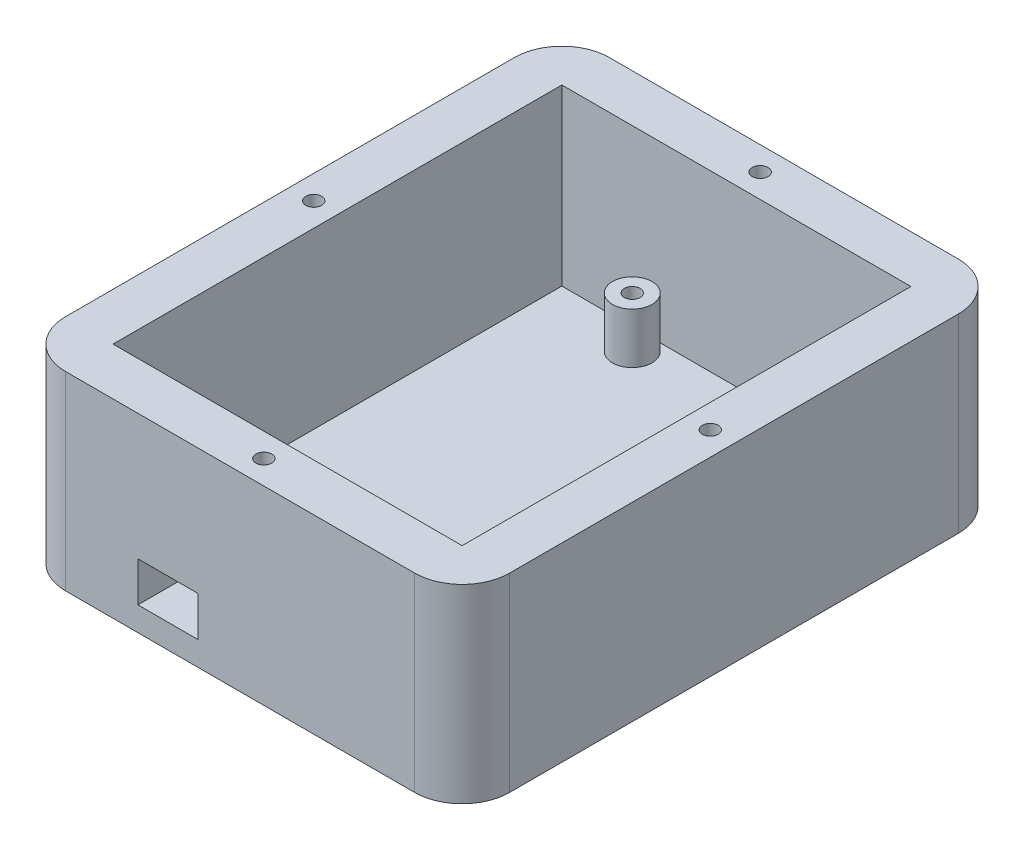
SolidWorks part; units mm, degrees
ref_plane "Front Plane" through (0, 0, 0) normal (0, 0, 1) x (1, 0, 0)
ref_plane "Top Plane" through (0, 0, 0) normal (0, 1, 0) x (1, 0, 0)
ref_plane "Right Plane" through (0, 0, 0) normal (1, 0, 0) x (0, 0, -1)
sketch "Sketch1" plane through (0, 0, 0) normal (0, 1, 0) x (1, 0, 0)
  line L1 (3.175, 0) -> (73.175, 0)
  line L2 (0, 3.175) -> (0, 93.175)
  line L3 (3.175, 96.35) -> (73.175, 96.35)
  line L4 (76.35, 3.175) -> (76.35, 93.175)
  arc A0 (3.175, 0) -> (0, 3.175) centre (3.175, 3.175) cw
  arc A1 (73.175, 0) -> (76.35, 3.175) centre (73.175, 3.175) ccw
  arc A2 (73.175, 96.35) -> (76.35, 93.175) centre (73.175, 93.175) cw
  arc A3 (0, 93.175) -> (3.175, 96.35) centre (3.175, 93.175) cw
  point P7 (0, 0)
  point P10 (76.35, 0)
  point P13 (76.35, 96.35)
  dimension "D3" = 3.175
  dimension "D1" = 76.35
  dimension "D2" = 96.35
extrude "Boss-Extrude1" add sketch "Sketch1" along normal blind 38.1
sketch "Sketch2" plane through (0, 38.1, 0) normal (0, 1, 0) x (1, 0, 0)
  line L8 (3.175, 3.175) -> (73.175, 3.175)
  line L9 (73.175, 3.175) -> (73.175, 93.175)
  line L10 (73.175, 93.175) -> (3.175, 93.175)
  line L11 (3.175, 93.175) -> (3.175, 3.175)
  line L12 (3.175, 3.175) -> (73.175, 3.175)
  line L13 (73.175, 3.175) -> (73.175, 93.175)
  line L14 (73.175, 93.175) -> (3.175, 93.175)
  line L15 (3.175, 93.175) -> (3.175, 3.175)
  dimension "D1" = 3.175
extrude "Cut-Extrude1" cut sketch "Sketch2" against normal offset from surface (34.925 mm away) 3.175 up to face at (38.175, 0, -48.175)
sketch "Sketch3" plane through (0, 3.175, 0) normal (0, 1, 0) x (1, 0, 0)
  line L0 (3.175, 93.175) -> (3.175, 3.175) construction
  line L1 (5.988, 92.175) -> (70.362, 92.175) construction
  line L2 (5.988, 92.175) -> (5.988, 4.175) construction
  line L3 (5.988, 4.175) -> (70.362, 4.175) construction
  line L4 (70.362, 92.175) -> (70.362, 4.175) construction
  line L5 (73.175, 93.175) -> (3.175, 93.175) construction
  circle A0 centre (39.988, 9.175) radius 1.5875
  circle A1 centre (21.588, 88.875) radius 1.5875
  circle A2 centre (21.588, 88.875) radius 3.9688
  circle A3 centre (39.988, 9.175) radius 3.9687
  point P6 (3.175, 48.175)
  point P7 (5.988, 48.175)
  point P10 (38.175, 93.175)
  point P11 (38.175, 92.175)
  dimension "D3" = 3.175
  dimension "D8" = 7.9375
  dimension "D9" = 7.9375
  dimension "D1" = 64.374
  dimension "D2" = 88
  dimension "D4" = 5
  dimension "D5" = 34
  dimension "D6" = 84.7
  dimension "D7" = 15.6
extrude "Boss-Extrude2" add sketch "Sketch3" along normal blind 10.16
sketch "Sketch4" plane through (0, 0, 0) normal (0, -1, 0) x (1, 0, 0)
  line L0 (-6.35, -3.175) -> (-6.35, -93.175)
  line L1 (3.175, -102.7) -> (73.175, -102.7)
  line L2 (82.7, -93.175) -> (82.7, -3.175)
  line L3 (73.175, 6.35) -> (3.175, 6.35)
  line L4 (0, -3.175) -> (0, -93.175)
  line L5 (3.175, -96.35) -> (73.175, -96.35)
  line L6 (76.35, -93.175) -> (76.35, -3.175)
  line L7 (73.175, 0) -> (3.175, 0)
  line L8 (0, -3.175) -> (0, -93.175)
  line L9 (3.175, -96.35) -> (73.175, -96.35)
  line L10 (76.35, -93.175) -> (76.35, -3.175)
  line L11 (73.175, 0) -> (3.175, 0)
  arc A0 (3.175, 6.35) -> (-6.35, -3.175) centre (3.175, -3.175) ccw
  arc A1 (-6.35, -93.175) -> (3.175, -102.7) centre (3.175, -93.175) ccw
  arc A2 (73.175, -102.7) -> (82.7, -93.175) centre (73.175, -93.175) ccw
  arc A3 (82.7, -3.175) -> (73.175, 6.35) centre (73.175, -3.175) ccw
  arc A4 (3.175, 0) -> (0, -3.175) centre (3.175, -3.175) ccw
  arc A5 (0, -93.175) -> (3.175, -96.35) centre (3.175, -93.175) ccw
  arc A6 (73.175, -96.35) -> (76.35, -93.175) centre (73.175, -93.175) ccw
  arc A7 (76.35, -3.175) -> (73.175, 0) centre (73.175, -3.175) ccw
  arc A8 (3.175, 0) -> (0, -3.175) centre (3.175, -3.175) ccw
  arc A9 (0, -93.175) -> (3.175, -96.35) centre (3.175, -93.175) ccw
  arc A10 (73.175, -96.35) -> (76.35, -93.175) centre (73.175, -93.175) ccw
  arc A11 (76.35, -3.175) -> (73.175, 0) centre (73.175, -3.175) ccw
  dimension "D1" = 0
  dimension "D2" = 6.35
extrude "Boss-Extrude3" add sketch "Sketch4" against normal up to surface (38.1 mm away) up to face at (38.175, 38.1, -48.175)
sketch "Sketch5" plane through (0, 38.1, 0) normal (0, 1, 0) x (1, 0, 0)
  line L0 (-6.35, 48.175) -> (3.175, 48.175) construction
  line L1 (-6.35, 93.175) -> (-6.35, 3.175) construction
  line L2 (3.175, 93.175) -> (3.175, 3.175) construction
  line L3 (38.175, 102.7) -> (38.175, 93.175) construction
  line L4 (73.175, 102.7) -> (3.175, 102.7) construction
  line L5 (73.175, 93.175) -> (3.175, 93.175) construction
  line L6 (38.175, 93.175) -> (38.175, -1.5718) construction
  line L7 (38.175, -1.5718) -> (3.175, 48.175) construction
  line L8 (3.175, 48.175) -> (73.175, 48.175) construction
  line L9 (73.175, 3.175) -> (73.175, 93.175) construction
  circle A0 centre (-1.5875, 48.175) radius 1.5875
  circle A1 centre (38.175, 97.9375) radius 1.5875
  circle A2 centre (38.175, -1.5875) radius 1.5875
  circle A3 centre (77.9375, 48.175) radius 1.5875
  point P16 (38.175, 97.9375)
  point P17 (-1.5875, 48.175)
  dimension "D1" = 3.175
  dimension "D2" = 3.175
extrude "Cut-Extrude2" cut sketch "Sketch5" against normal blind 12.7
sketch "Sketch6" plane through (0, 38.1, 0) normal (0, 1, 0) x (1, 0, 0)
  line L4 (3.175, -6.35) -> (73.175, -6.35)
  line L5 (82.7, 3.175) -> (82.7, 93.175)
  line L6 (73.175, 102.7) -> (3.175, 102.7)
  line L7 (-6.35, 93.175) -> (-6.35, 3.175)
  line L8 (3.175, -6.35) -> (73.175, -6.35)
  line L9 (82.7, 3.175) -> (82.7, 93.175)
  line L10 (73.175, 102.7) -> (3.175, 102.7)
  line L11 (-6.35, 93.175) -> (-6.35, 3.175)
  circle A0 centre (38.175, -1.5875) radius 1.5875 construction
  circle A1 centre (77.9375, 48.175) radius 1.5875 construction
  circle A2 centre (38.175, 97.9375) radius 1.5875 construction
  circle A3 centre (-1.5875, 48.175) radius 1.5875 construction
  arc A4 (-6.35, 3.175) -> (3.175, -6.35) centre (3.175, 3.175) ccw
  arc A5 (73.175, -6.35) -> (82.7, 3.175) centre (73.175, 3.175) ccw
  arc A6 (82.7, 93.175) -> (73.175, 102.7) centre (73.175, 93.175) ccw
  arc A7 (3.175, 102.7) -> (-6.35, 93.175) centre (3.175, 93.175) ccw
  arc A8 (-6.35, 3.175) -> (3.175, -6.35) centre (3.175, 3.175) ccw
  arc A9 (73.175, -6.35) -> (82.7, 3.175) centre (73.175, 3.175) ccw
  arc A10 (82.7, 93.175) -> (73.175, 102.7) centre (73.175, 93.175) ccw
  arc A11 (3.175, 102.7) -> (-6.35, 93.175) centre (3.175, 93.175) ccw
  circle A12 centre (38.175, -1.5875) radius 1.5875
  circle A13 centre (77.9375, 48.175) radius 1.5875
  circle A14 centre (38.175, 97.9375) radius 1.5875
  circle A15 centre (-1.5875, 48.175) radius 1.5875
  dimension "D1" = 0
sketch "Sketch7" plane through (0, 0, 6.35) normal (0, 0, 1) x (1, 0, 0)
  line L0 (43.9567, 13.335) -> (36.0192, 13.335) construction
  line L1 (43.9567, 13.335) -> (36.0192, 13.335) construction
  line L2 (17.688, 8.835) -> (29.688, 8.835) construction
  line L3 (17.688, 12.835) -> (29.688, 12.835)
  line L4 (17.688, 12.835) -> (17.688, 4.835)
  line L5 (17.688, 4.835) -> (29.688, 4.835)
  line L6 (29.688, 12.835) -> (29.688, 4.835)
  line L7 (29.688, 8.835) -> (23.688, 12.835) construction
  line L8 (23.688, 12.835) -> (23.688, 4.835) construction
  point P8 (39.988, 13.335)
  point P11 (23.688, 8.835)
  dimension "D1" = 12
  dimension "D2" = 8
  dimension "D3" = 1
  dimension "D4" = 16.3
extrude "Cut-Extrude3" cut sketch "Sketch7" against normal up to surface (9.525 mm away) up to face at (38.175, 20.6375, -3.175)
